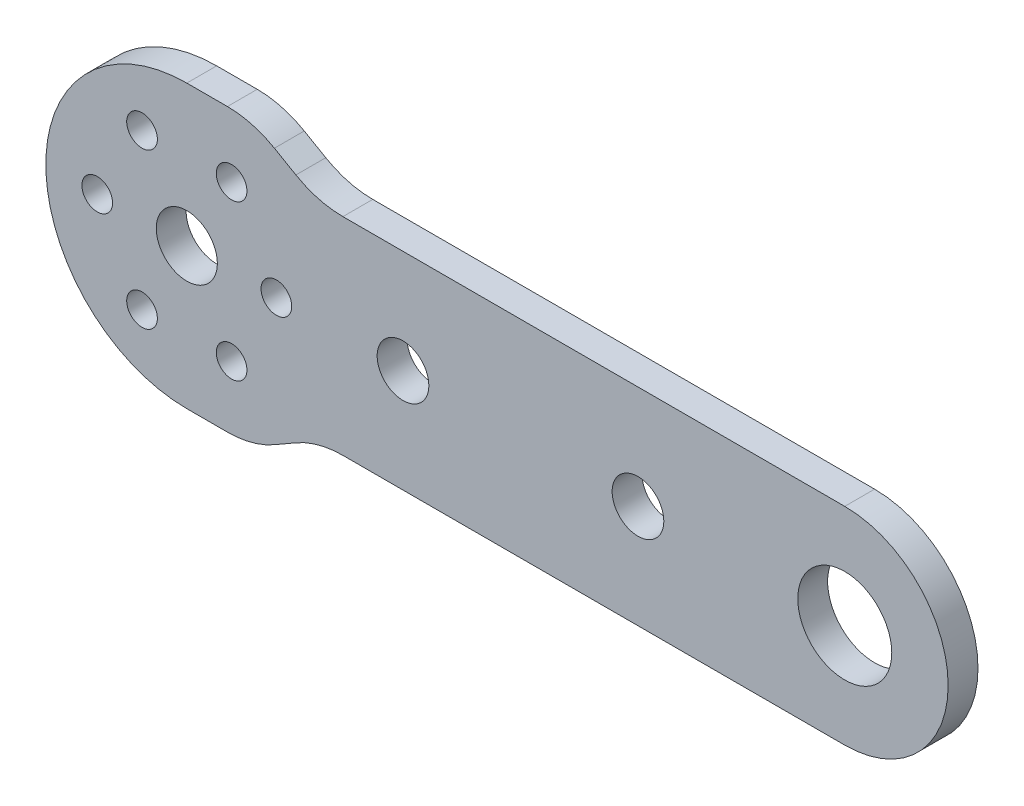
SolidWorks part; units mm, degrees
material "ABS"
ref_plane "Alzado" through (0, 0, 0) normal (0, 0, 1) x (1, 0, 0)
ref_plane "Planta" through (0, 0, 0) normal (0, 1, 0) x (1, 0, 0)
ref_plane "Vista lateral" through (0, 0, 0) normal (1, 0, 0) x (0, 0, -1)
sketch "Croquis1" plane through (0, 0, 86.2039) normal (0, 0, 1) x (1, 0, 0)
  line L0 (0, -15) -> (7, -15)
  line L1 (7, -15) -> (13.9282, -11)
  line L2 (13.9282, -11) -> (70, -11)
  line L4 (13.9282, 11) -> (70, 11)
  line L5 (13.9282, 11) -> (7, 15)
  line L6 (7, 15) -> (0, 15)
  line L7 (-15, 0) -> (81, 0) construction
  arc A0 (0, 15) -> (0, -15) centre (0, 0) ccw
  arc A1 (70, 11) -> (70, -11) centre (70, 0) cw
  circle A2 centre (70, 0) radius 5
  circle A3 centre (0, 0) radius 3.25
  dimension "D1" = 15
  dimension "D5" = 6.5
  dimension "D7" = 10
  dimension "D3" = 70
  dimension "D6" = 11
  dimension "D2" = 30
  dimension "D4" = 7
extrude "Saliente-Extruir1" add sketch "Croquis1" along normal blind 3.175
hole_wizard "Taladro de margen para #41" positions "Croquis3" profile "Croquis2" hole size "#4" standard "Ansi Inch"
sketch "Croquis3" plane through (0, 0, 89.3789) normal (0, 0, 1) x (1, 0, 0)
  circle A2 centre (0, 0) radius 9.53 construction
  point P35 (9.53, 0)
  point P43 (4.765, -8.2532)
  point P44 (-4.765, -8.2532)
  point P45 (-9.53, 0)
  point P46 (-4.765, 8.2532)
  point P47 (4.765, 8.2532)
  dimension "D1" = 19.06
  dimension "D2" = 6
sketch "Croquis2" plane through (9.53, 0, 89.3789) normal (1, 0, 0) x (0, -1, 0)
  line L0 (0, 0) -> (0, 10.9806)
  line L1 (0, 10.9806) -> (1.6319, 10)
  line L2 (1.6319, 10) -> (1.6319, 0)
  line L5 (1.6319, 0) -> (0, 0)
  line L10 (0, 10.9806) -> (-1.6319, 10) construction
  line L11 (0, -6.35) -> (0, 107.95) construction
  dimension "Diámetro de taladro" = 3.2639
  dimension "Profundidad de taladro" = 10
  dimension "Ángulo de perforador" = 118
hole_wizard "Taladro de margen para M51" positions "Croquis5" profile "Croquis4" hole size "M5" standard "Ansi Metric"
sketch "Croquis5" plane through (0, 0, 89.3789) normal (0, 0, 1) x (1, 0, 0)
  point P0 (23, 0)
  point P2 (48, 0)
  dimension "D1" = 23
  dimension "D2" = 25
sketch "Croquis4" plane through (23, 0, 89.3789) normal (1, 0, 0) x (0, -1, 0)
  line L0 (0, 0) -> (0, 7.6524)
  line L1 (0, 7.6524) -> (2.75, 6)
  line L2 (2.75, 6) -> (2.75, 0)
  line L5 (2.75, 0) -> (0, 0)
  line L10 (0, 7.6524) -> (-2.75, 6) construction
  line L11 (0, -6.35) -> (0, 107.95) construction
  dimension "Diámetro de taladro" = 5.5
  dimension "Profundidad de taladro" = 6
  dimension "Ángulo de perforador" = 118
fillet "Redondeo1" radius 10 4 edges at (7, 15, 87.7914) (13.9282, 11, 87.7914) (13.9282, -11, 87.7914) (7, -15, 87.7914)
